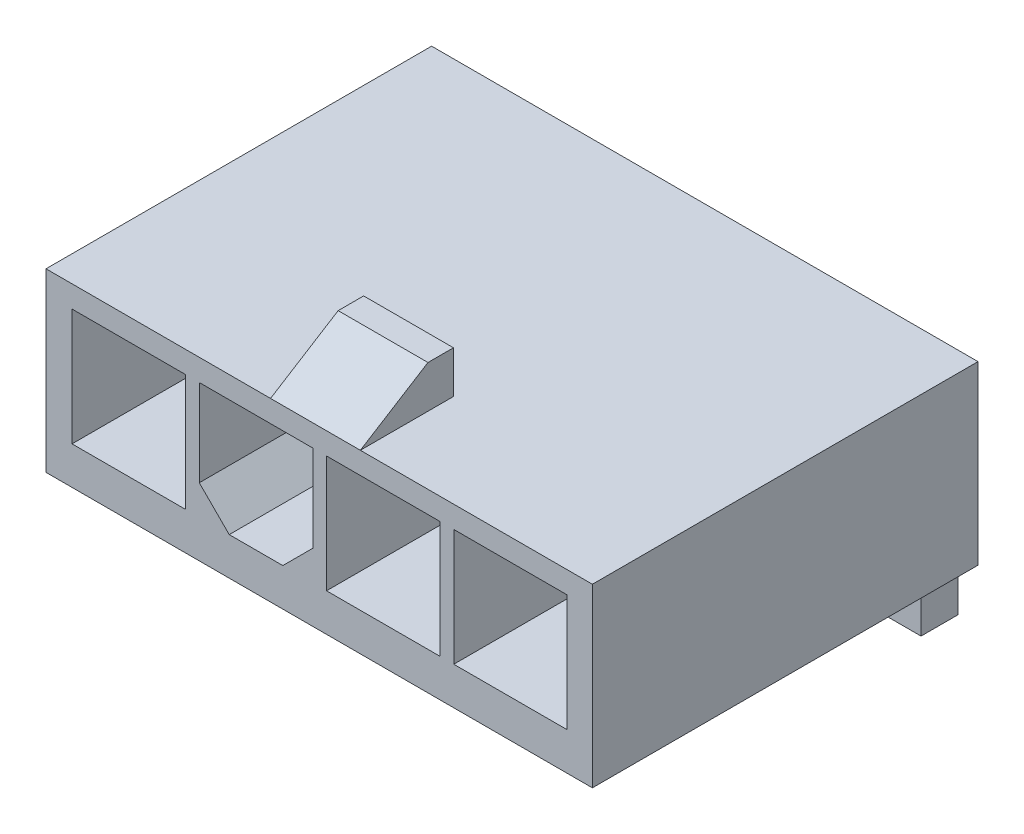
SolidWorks part; units mm, degrees
ref_plane "Front Plane" through (0, 0, 0) normal (0, 0, 1) x (1, 0, 0)
ref_plane "Top Plane" through (0, 0, 0) normal (0, 1, 0) x (1, 0, 0)
ref_plane "Right Plane" through (0, 0, 0) normal (1, 0, 0) x (0, 0, -1)
sketch "Sketch1" plane through (0, 0, 0) normal (0, 1, 0) x (1, 0, 0)
  line L1 (0, 0) -> (18.25, 0)
  line L2 (0, 0) -> (0, 12.88)
  line L3 (0, 12.88) -> (18.25, 12.88)
  line L4 (18.25, 0) -> (18.25, 12.88)
extrude "Boss-Extrude1" add sketch "Sketch1" along normal blind 5.89
sketch "Sketch2" plane through (0, 0, 0) normal (0, 0, 1) x (1, 0, 0)
  line L0 (4.66, 5.1605) -> (5.12, 5.1605) construction
  line L1 (0.87, 5.1605) -> (4.66, 5.1605)
  line L2 (0.87, 5.1605) -> (0.87, 1.2605)
  line L3 (0.87, 1.2605) -> (4.66, 1.2605)
  line L4 (4.66, 5.1605) -> (4.66, 1.2605)
  line L5 (5.12, 5.1605) -> (8.91, 5.1605)
  line L6 (5.12, 5.1605) -> (5.12, 1.2605) construction
  line L7 (5.12, 1.2605) -> (8.91, 1.2605) construction
  line L8 (8.91, 5.1605) -> (8.91, 1.2605) construction
  line L9 (9.37, 5.1605) -> (13.16, 5.1605)
  line L10 (9.37, 5.1605) -> (9.37, 1.2605)
  line L11 (9.37, 1.2605) -> (13.16, 1.2605)
  line L12 (13.16, 5.1605) -> (13.16, 1.2605)
  line L13 (13.62, 5.1605) -> (17.41, 5.1605)
  line L14 (13.62, 5.1605) -> (13.62, 1.2605)
  line L15 (13.62, 1.2605) -> (17.41, 1.2605)
  line L16 (17.41, 5.1605) -> (17.41, 1.2605)
  line L17 (8.91, 5.1605) -> (9.37, 5.1605) construction
  line L18 (13.16, 5.1605) -> (13.62, 5.1605) construction
  line L19 (4.66, 1.2605) -> (5.12, 1.2605) construction
  line L20 (8.91, 1.2605) -> (9.37, 1.2605) construction
  line L21 (5.12, 2.2605) -> (6.12, 1.2605)
  line L22 (13.16, 1.2605) -> (13.62, 1.2605) construction
  line L23 (5.12, 5.1605) -> (5.12, 2.2605)
  line L24 (6.12, 1.2605) -> (7.91, 1.2605)
  line L25 (7.91, 1.2605) -> (8.91, 2.2605)
  line L26 (8.91, 2.2605) -> (8.91, 5.1605)
extrude "Cut-Extrude1" cut sketch "Sketch2" against normal blind 9
sketch "Sketch3" plane through (0, 5.89, 0) normal (0, 1, 0) x (1, 0, 0)
  line L0 (0, 0) -> (18.25, 0) construction
  line L1 (7.5, 0) -> (10.5, 0)
  line L2 (7.5, 0) -> (7.5, 3.11)
  line L3 (7.5, 3.11) -> (10.5, 3.11)
  line L4 (10.5, 0) -> (10.5, 3.11)
extrude "Boss-Extrude2" add sketch "Sketch3" along normal blind 1.41
sketch "Sketch4" plane through (7.5, 0, 0) normal (-1, 0, 0) x (0, 0, 1)
  line L0 (-2.2584, 7.3) -> (0, 5.89)
  line L1 (-3.11, 7.3) -> (0, 7.3) construction
  line L2 (0, 7.3) -> (0, 5.89) construction
  line L3 (0, 5.89) -> (0, 7.3)
  line L4 (0, 7.3) -> (-2.2584, 7.3)
extrude "Cut-Extrude2" cut sketch "Sketch4" against normal blind 3
sketch "Sketch5" plane through (0, 0, -12.88) normal (0, 0, -1) x (-1, 0, 0)
  line L1 (-3.4, 3.26) -> (-2.17, 3.26)
  line L2 (-3.4, 3.26) -> (-3.4, 2.03)
  line L3 (-3.4, 2.03) -> (-2.17, 2.03)
  line L4 (-2.17, 3.26) -> (-2.17, 2.03)
  line L18 (-7.6052, 3.2578) -> (-6.3752, 3.2578)
  line L19 (-7.6052, 3.2578) -> (-7.6052, 2.0278)
  line L20 (-7.6052, 2.0278) -> (-6.3752, 2.0278)
  line L21 (-6.3752, 3.2578) -> (-6.3752, 2.0278)
  line L22 (-11.8105, 3.2556) -> (-10.5805, 3.2556)
  line L23 (-11.8105, 3.2556) -> (-11.8105, 2.0256)
  line L24 (-11.8105, 2.0256) -> (-10.5805, 2.0256)
  line L25 (-10.5805, 3.2556) -> (-10.5805, 2.0256)
  line L26 (-16.0157, 3.2535) -> (-14.7857, 3.2535)
  line L27 (-16.0157, 3.2535) -> (-16.0157, 2.0235)
  line L28 (-16.0157, 2.0235) -> (-14.7857, 2.0235)
  line L29 (-14.7857, 3.2535) -> (-14.7857, 2.0235)
  dimension "D1" = 4
sketch "Sketch7" plane through (0, 0, 0) normal (-1, 0, 0) x (0, 0, 1)
  line L0 (-4.3, 2.72) -> (-12.7005, 2.72)
  line L1 (-13.88, 1.5405) -> (-13.88, -3.3375)
  arc A0 (-12.7005, 2.72) -> (-13.88, 1.5405) centre (-12.7005, 1.5405) ccw
ref_plane "Plane1" through (0, -3.3375, 0) normal (0, -1, 0) x (1, 0, 0)
sketch "Sketch8" plane through (0, -3.3375, 0) normal (0, -1, 0) x (1, 0, 0)
  line L1 (14.7821, -13.2152) -> (16.0121, -13.2152)
  line L2 (14.7821, -13.2152) -> (14.7821, -14.4452)
  line L3 (14.7821, -14.4452) -> (16.0121, -14.4452)
  line L4 (16.0121, -13.2152) -> (16.0121, -14.4452)
  line L18 (10.5768, -13.2174) -> (11.8068, -13.2174)
  line L19 (10.5768, -13.2174) -> (10.5768, -14.4474)
  line L20 (10.5768, -14.4474) -> (11.8068, -14.4474)
  line L21 (11.8068, -13.2174) -> (11.8068, -14.4474)
  line L22 (6.3716, -13.2196) -> (7.6016, -13.2196)
  line L23 (6.3716, -13.2196) -> (6.3716, -14.4496)
  line L24 (6.3716, -14.4496) -> (7.6016, -14.4496)
  line L25 (7.6016, -13.2196) -> (7.6016, -14.4496)
  line L26 (2.1663, -13.2217) -> (3.3963, -13.2217)
  line L27 (2.1663, -13.2217) -> (2.1663, -14.4517)
  line L28 (2.1663, -14.4517) -> (3.3963, -14.4517)
  line L29 (3.3963, -13.2217) -> (3.3963, -14.4517)
  dimension "D1" = 4
extrude "Cut-Extrude3" cut sketch "Sketch5" against normal blind 4
sweep "Sweep2" add profiles "Sketch8" path "Sketch7"
